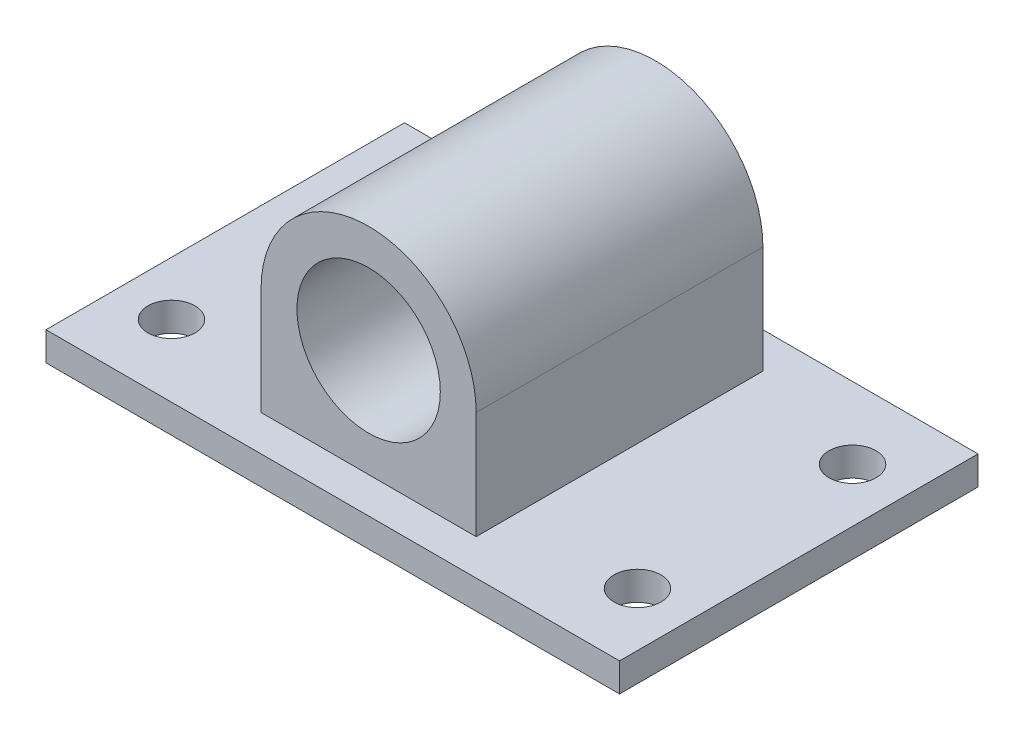
SolidWorks part; units mm, degrees
ref_plane "Front Plane" through (0, 0, 0) normal (0, 0, 1) x (1, 0, 0)
ref_plane "Top Plane" through (0, 0, 0) normal (0, 1, 0) x (1, 0, 0)
ref_plane "Right Plane" through (0, 0, 0) normal (1, 0, 0) x (0, 0, -1)
sketch "Sketch1" plane through (0, 0, 0) normal (0, 1, 0) x (1, 0, 0)
  line L1 (-50.8, -31.75) -> (50.8, -31.75)
  line L2 (-50.8, -31.75) -> (-50.8, 31.75)
  line L3 (-50.8, 31.75) -> (50.8, 31.75)
  line L4 (50.8, -31.75) -> (50.8, 31.75)
  line L5 (-50.8, -31.75) -> (50.8, 31.75) construction
  line L6 (-50.8, 31.75) -> (50.8, -31.75) construction
  point P0 (0, 0)
  dimension "D1" = 101.6
  dimension "D2" = 63.5
extrude "Boss-Extrude1" add sketch "Sketch1" along normal blind 5.08
sketch "Sketch2" plane through (0, 0, 0) normal (0, 1, 0) x (1, 0, 0)
  line L0 (-50.8, 0) -> (50.8, 0) construction
  line L1 (-50.8, 31.75) -> (-50.8, -31.75) construction
  line L2 (50.8, -31.75) -> (50.8, 31.75) construction
  line L3 (0, 31.75) -> (0, -31.75) construction
  line L4 (50.8, 31.75) -> (-50.8, 31.75) construction
  line L5 (-50.8, -31.75) -> (50.8, -31.75) construction
  circle A0 centre (-41.275, 19.05) radius 4.1656
  circle A1 centre (41.275, 19.05) radius 4.1656
  circle A2 centre (41.275, -19.05) radius 4.1656
  circle A3 centre (-41.275, -19.05) radius 4.1656
  point P20 (0, 0)
  point P21 (0, 0)
  point P22 (0, 0)
  dimension "D1" = 8.3312
  dimension "D2" = 82.55
  dimension "D3" = 38.1
extrude "Cut-Extrude1" cut sketch "Sketch2" along normal through all
ref_plane "Plane1" through (0, 0, 0) normal (0, 0, 1) x (1, 0, 0)
sketch "Sketch3" plane through (0, 0, 0) normal (0, 0, 1) x (1, 0, 0)
  line L0 (0, 0) -> (0, 47.3526) construction
  line L1 (-50.8, 5.08) -> (50.8, 5.08) construction
  line L2 (-19.05, 24.13) -> (-19.05, 5.08)
  line L3 (-19.05, 5.08) -> (19.05, 5.08)
  line L4 (19.05, 5.08) -> (19.05, 24.13)
  circle A0 centre (0, 24.13) radius 12.7
  arc A1 (19.05, 24.13) -> (-19.05, 24.13) centre (0, 24.13) ccw
  dimension "D1" = 25.4
  dimension "D3" = 38.1
  dimension "D2" = 19.05
extrude "Boss-Extrude2" add sketch "Sketch3" along normal mid plane 50.8
